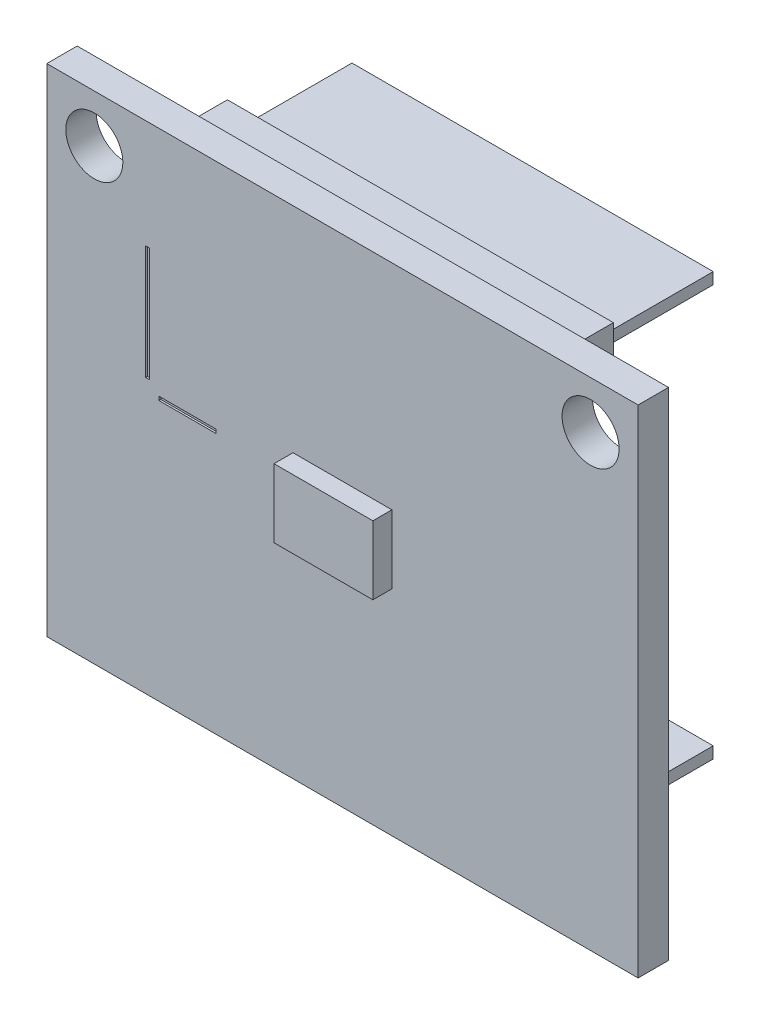
SolidWorks part; units mm, degrees
ref_plane "Top Plane" through (0, 0, 0) normal (0, 0, 1) x (1, 0, 0)
ref_plane "Right Plane" through (0, 0, 0) normal (0, 1, 0) x (1, 0, 0)
ref_plane "Front Plane" through (0, 0, 0) normal (1, 0, 0) x (0, 0, -1)
sketch "Sketch1" plane through (0, 0, 0) normal (0, 0, 1) x (1, 0, 0)
  line L0 (0, 13.05) -> (0, -13.05) construction
  line L1 (-15.55, 13.05) -> (15.55, 13.05)
  line L2 (-15.55, 13.05) -> (-15.55, -13.05)
  line L3 (-15.55, -13.05) -> (15.55, -13.05)
  line L4 (15.55, 13.05) -> (15.55, -13.05)
  line L5 (-15.55, 13.05) -> (15.55, -13.05) construction
  dimension "D1" = 31.1
  dimension "D2" = 26.1
extrude "Boss-Extrude1" add sketch "Sketch1" along normal mid plane 1.6
sketch "Sketch2" plane through (0, 0, -0.8) normal (0, 0, -1) x (-1, 0, 0)
  line L1 (15.55, -13.05) -> (-15.55, -13.05) construction
  line L2 (-10.15, -9.55) -> (10.15, -9.55)
  line L3 (-10.15, -9.55) -> (-10.15, -12.05)
  line L4 (-10.15, -12.05) -> (10.15, -12.05)
  line L5 (10.15, -9.55) -> (10.15, -12.05)
  line L6 (0, 0) -> (0, -12.05) construction
  line L7 (-15.55, 0) -> (15.55, 0) construction
  line L8 (-15.55, -13.05) -> (-15.55, 13.05) construction
  line L9 (15.55, 13.05) -> (15.55, -13.05) construction
  line L10 (10.15, 9.55) -> (10.15, 12.05)
  line L11 (-10.15, 12.05) -> (10.15, 12.05)
  line L12 (-10.15, 9.55) -> (-10.15, 12.05)
  line L13 (-10.15, 9.55) -> (10.15, 9.55)
  dimension "D1" = 1
  dimension "D2" = 2.5
  dimension "D3" = 20.3
extrude "Boss-Extrude2" add sketch "Sketch2" along normal blind 2.5
sketch "Sketch3" plane through (0, 0, -3.3) normal (0, 0, -1) x (-1, 0, 0)
  line L0 (0, 10.5) -> (0, 9.55) construction
  line L1 (-9.5, 11.1) -> (9.5, 11.1)
  line L2 (-9.5, 11.1) -> (-9.5, 10.5)
  line L3 (-9.5, 10.5) -> (9.5, 10.5)
  line L4 (9.5, 11.1) -> (9.5, 10.5)
  line L5 (-10.15, 9.55) -> (10.15, 9.55) construction
  line L6 (0, 12.05) -> (0, 11.1) construction
  line L7 (10.15, 12.05) -> (-10.15, 12.05) construction
  line L8 (-15.55, 0) -> (15.55, 0) construction
  line L9 (-15.55, -13.05) -> (-15.55, 13.05) construction
  line L10 (15.55, 13.05) -> (15.55, -13.05) construction
  line L11 (9.5, -11.1) -> (9.5, -10.5)
  line L12 (-9.5, -10.5) -> (9.5, -10.5)
  line L13 (-9.5, -11.1) -> (-9.5, -10.5)
  line L14 (-9.5, -11.1) -> (9.5, -11.1)
  dimension "D1" = 0.6
  dimension "D2" = 19
extrude "Boss-Extrude3" add sketch "Sketch3" along normal blind 6.1
chamfer "Chamfer1" distance 0.2 angle 45 8 edges at (9.5, -10.8, -9.4) (0, -10.5, -9.4) (-9.5, -10.8, -9.4) (0, -11.1, -9.4) (0, 11.1, -9.4) (-9.5, 10.8, -9.4) (0, 10.5, -9.4) (9.5, 10.8, -9.4)
sketch "Sketch4" plane through (0, 0, 0.8) normal (0, 0, 1) x (1, 0, 0)
  line L0 (-2.6, -1.8) -> (2.6, 1.8) construction
  line L1 (-2.6, -1.8) -> (2.6, -1.8)
  line L2 (-2.6, -1.8) -> (-2.6, 1.8)
  line L3 (-2.6, 1.8) -> (2.6, 1.8)
  line L4 (2.6, -1.8) -> (2.6, 1.8)
  dimension "D1" = 3.6
  dimension "D2" = 5.2
extrude "Boss-Extrude4" add sketch "Sketch4" along normal blind 1
sketch "Sketch5" plane through (0, 0, 0.8) normal (0, 0, 1) x (1, 0, 0)
  line L0 (-10.35, 1.35) -> (-9.65, 0.65) construction
  line L1 (-10.35, 7.35) -> (-10.15, 7.35)
  line L2 (-10.35, 7.35) -> (-10.35, 1.35)
  line L3 (-10.35, 1.35) -> (-10.15, 1.35)
  line L4 (-10.15, 7.35) -> (-10.15, 1.35)
  line L5 (-9.65, 0.85) -> (-6.65, 0.85)
  line L6 (-9.65, 0.85) -> (-9.65, 0.65)
  line L7 (-9.65, 0.65) -> (-6.65, 0.65)
  line L8 (-6.65, 0.85) -> (-6.65, 0.65)
  point P8 (-10, 1)
  dimension "D1" = 0.2
  dimension "D2" = 6
  dimension "D3" = 3
  dimension "D4" = 0.5
  dimension "D5" = 0.5
  dimension "D6" = 10
  dimension "D7" = 1
extrude "Cut-Extrude1" cut sketch "Sketch5" against normal blind 0.1
sketch "Sketch6" plane through (0, 0, 0.8) normal (0, 0, 1) x (1, 0, 0)
  line L0 (0, 13.05) -> (0, -13.05) construction
  line L1 (15.55, 13.05) -> (-15.55, 13.05) construction
  line L2 (-15.55, -13.05) -> (15.55, -13.05) construction
  line L3 (-15.55, 13.05) -> (-15.55, -13.05) construction
  circle A0 centre (-13.05, 10.55) radius 1.5
  circle A1 centre (13.05, 10.55) radius 1.5
  dimension "D1" = 2.5
  dimension "D2" = 3
  dimension "D3" = 2.5
extrude "Cut-Extrude2" cut sketch "Sketch6" against normal through all
